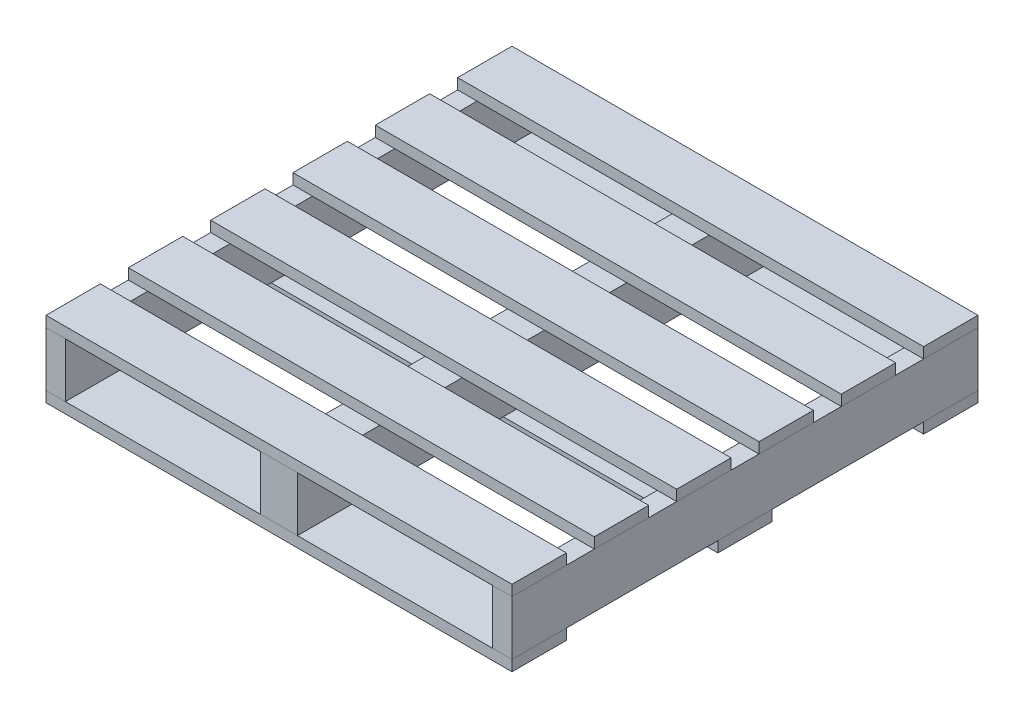
SolidWorks part; units mm, degrees
ref_plane "Front Plane" through (0, 0, 0) normal (0, 0, 1) x (1, 0, 0)
ref_plane "Top Plane" through (0, 0, 0) normal (0, 1, 0) x (1, 0, 0)
ref_plane "Right Plane" through (0, 0, 0) normal (1, 0, 0) x (0, 0, -1)
sketch "Sketch1" plane through (0, 0, 0) normal (0, 0, 1) x (1, 0, 0)
  line L0 (-381, 0) -> (381, 0) construction
  line L5 (-381, 61.976) -> (-381, -61.976) construction
  line L6 (381, 61.976) -> (381, -61.976) construction
  line L11 (-381, -61.976) -> (381, -61.976) construction
  line L12 (-381, 61.976) -> (381, 61.976) construction
  line L13 (-349.25, 61.976) -> (-349.25, -61.976) construction
  line L14 (349.25, 61.976) -> (349.25, -61.976) construction
  line L15 (-30.226, 61.976) -> (-30.226, -61.976) construction
  line L16 (30.226, -61.976) -> (30.226, 61.976) construction
  line L17 (0, 61.976) -> (0, -61.976) construction
  line L18 (-381, 0) -> (-349.25, 0)
  line L19 (-30.226, 0) -> (0, 0)
  line L20 (0, 0) -> (30.226, 0)
  line L21 (349.25, 0) -> (381, 0)
  line L22 (-381, 44.5008) -> (381, 44.5008) construction
  line L23 (-381, -44.5008) -> (381, -44.5008) construction
  point P3 (0, 0)
  point P6 (-381, 0)
  point P9 (381, 0)
  point P23 (0, 0)
  dimension "Overall Width" = 762
  dimension "Overall Height" = 123.952
  dimension "Maximum Fork Width" = 319.024
  dimension "D2" = 319.024
  dimension "Maximum Fork Height" = 89.0016
  dimension "D1" = 31.75
  dimension "D3" = 17.4752
sketch "Sketch2" plane through (0, 0, 0) normal (1, 0, 0) x (0, 0, -1)
  line L0 (381, 0) -> (-381, 0) construction
  point P4 (0, 0)
  dimension "Overall Depth" = 762
sketch "Sketch3" plane through (0, 0, 0) normal (0, 0, 1) x (1, 0, 0)
  line L0 (-349.25, 61.976) -> (-349.25, -61.976) construction
  line L1 (-381, 44.5008) -> (-349.25, 44.5008)
  line L2 (-381, 44.5008) -> (-381, -44.5008)
  line L3 (-381, -44.5008) -> (-349.25, -44.5008)
  line L4 (-349.25, 44.5008) -> (-349.25, -44.5008)
  line L5 (-381, -44.5008) -> (381, -44.5008) construction
  line L6 (-30.226, 61.976) -> (-30.226, -61.976) construction
  line L7 (-30.226, 44.5008) -> (30.226, 44.5008)
  line L8 (-30.226, 44.5008) -> (-30.226, -44.5008)
  line L9 (-30.226, -44.5008) -> (30.226, -44.5008)
  line L10 (30.226, 44.5008) -> (30.226, -44.5008)
  line L11 (-381, 44.5008) -> (381, 44.5008) construction
  line L12 (30.226, -61.976) -> (30.226, 61.976) construction
  line L13 (349.25, 61.976) -> (349.25, -61.976) construction
  line L14 (349.25, 44.5008) -> (381, 44.5008)
  line L15 (349.25, 44.5008) -> (349.25, -44.5008)
  line L16 (349.25, -44.5008) -> (381, -44.5008)
  line L17 (381, 44.5008) -> (381, -44.5008)
extrude "Boss-Extrude1" add sketch "Sketch3" along normal up to vertex (381 mm away) and the other way up to vertex (381 mm away) up to point (0, 0, 381) other way up to point (0, 0, -381)
sketch "Sketch4" plane through (0, 44.5008, 0) normal (0, 1, 0) x (1, 0, 0)
  line L0 (381, -381) -> (381, 381) construction
  line L1 (-381, -381) -> (381, -381)
  line L2 (-381, -381) -> (-381, -292.1)
  line L3 (-381, -292.1) -> (381, -292.1)
  line L4 (381, -381) -> (381, -292.1)
  line L5 (-381, -246.38) -> (381, -246.38)
  line L6 (-381, -246.38) -> (-381, -157.48)
  line L7 (-381, -157.48) -> (381, -157.48)
  line L8 (381, -246.38) -> (381, -157.48)
  line L9 (-381, -111.76) -> (381, -111.76)
  line L10 (-381, -111.76) -> (-381, -22.86)
  line L11 (-381, -22.86) -> (381, -22.86)
  line L12 (381, -111.76) -> (381, -22.86)
  line L13 (-381, 22.86) -> (381, 22.86)
  line L14 (-381, 22.86) -> (-381, 111.76)
  line L15 (-381, 111.76) -> (381, 111.76)
  line L16 (381, 22.86) -> (381, 111.76)
  line L17 (-381, 157.48) -> (381, 157.48)
  line L18 (-381, 157.48) -> (-381, 246.38)
  line L19 (-381, 246.38) -> (381, 246.38)
  line L20 (381, 157.48) -> (381, 246.38)
  line L21 (-381, -381) -> (-381, 381) construction
  line L22 (-381, 292.1) -> (381, 292.1)
  line L23 (-381, 292.1) -> (-381, 381)
  line L24 (-381, 381) -> (381, 381)
  line L25 (381, 292.1) -> (381, 381)
  dimension "D1" = 88.9
  dimension "D3" = 45.72
  dimension "Top Boards" = 6
extrude "Boss-Extrude2" add sketch "Sketch4" along normal up to vertex (17.4752 mm away) separate body up to point (-381, 61.976, 0)
sketch "Sketch5" plane through (0, -44.5008, 0) normal (0, -1, 0) x (1, 0, 0)
  line L0 (381, 381) -> (381, -381) construction
  line L1 (-381, 381) -> (381, 381)
  line L2 (-381, 381) -> (-381, 292.1)
  line L3 (-381, 292.1) -> (381, 292.1)
  line L4 (381, 381) -> (381, 292.1)
  line L5 (-381, -381) -> (381, -381)
  line L6 (-381, -381) -> (-381, -292.1)
  line L7 (-381, -292.1) -> (381, -292.1)
  line L8 (381, -381) -> (381, -292.1)
  line L9 (-381, -44.45) -> (381, -44.45)
  line L10 (-381, -44.45) -> (-381, 44.45)
  line L11 (-381, 44.45) -> (381, 44.45)
  line L12 (381, -44.45) -> (381, 44.45)
  line L13 (-381, -44.45) -> (381, 44.45) construction
  line L14 (-381, 44.45) -> (381, -44.45) construction
  line L16 (-381, 381) -> (-381, 292.1) construction
  line L17 (381, 381) -> (381, 292.1) construction
  point P12 (0, 0)
extrude "Boss-Extrude3" add sketch "Sketch5" along normal up to vertex (17.4752 mm away) separate body up to point (-381, -61.976, 0)
sketch "Sketch7" plane through (0, 0, 0) normal (0, 1, 0) x (1, 0, 0)
  line L0 (0, 381) -> (381, 381) construction
  line L2 (381, 381) -> (381, 0) construction
  line L3 (381, 0) -> (381, -381) construction
  line L4 (381, -381) -> (0, -381) construction
  line L5 (-381, -381) -> (381, -381) construction
  line L6 (-381, 381) -> (0, 381) construction
equation "\"D2@Sketch1\" = \"Maximum Fork Width@Sketch1\""
equation "\"D3@Sketch4\" =  ( \"Overall Depth@Sketch2\" -  ( 3.5 * \"Top Boards@Sketch4\" )  )  /  ( \"Top Boards@Sketch4\" - 1 ) "
